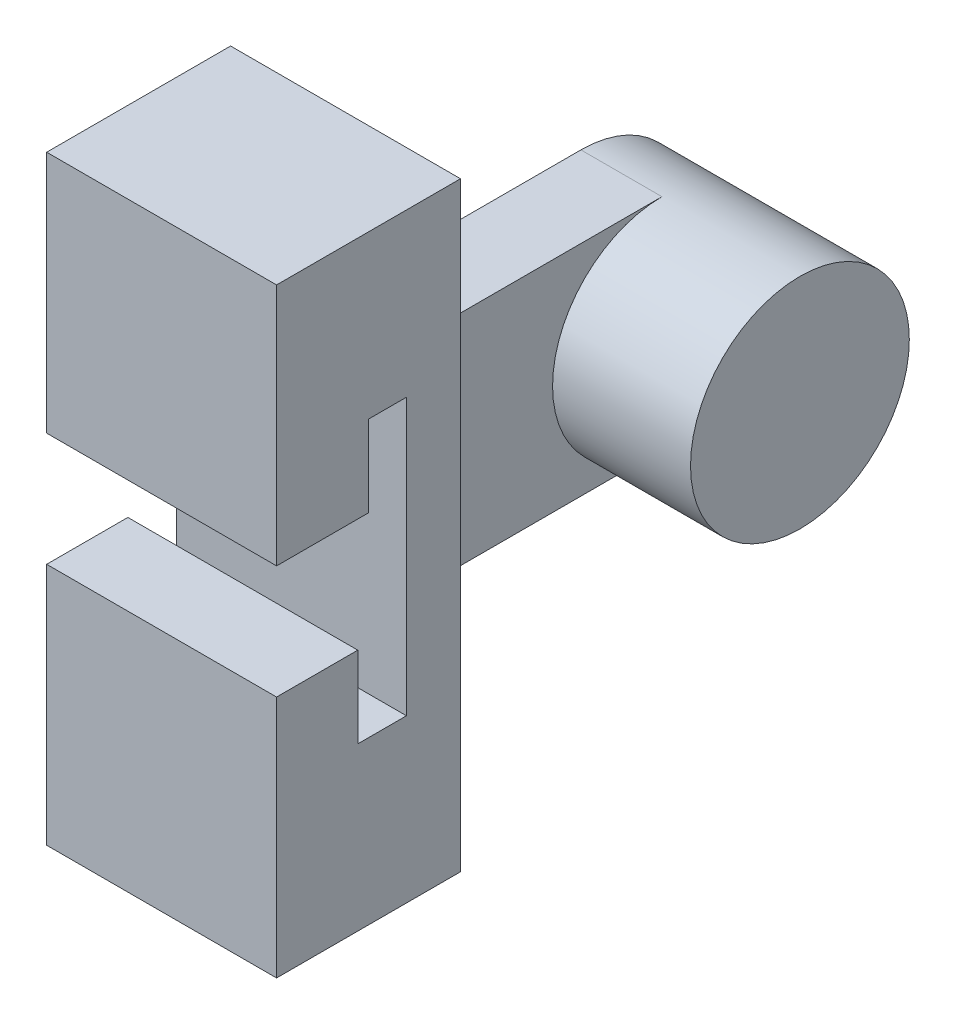
SolidWorks part; units mm, degrees
material "ASTM A36 Steel"
ref_plane "Front Plane" through (0, 0, 0) normal (1, 0, 0) x (0, 1, 0)
ref_plane "Top Plane" through (0, 0, 0) normal (0, 0, 1) x (0, 1, 0)
ref_plane "Right Plane" through (0, 0, 0) normal (0, 1, 0) x (-1, 0, 0)
sketch "Sketch1" plane through (0, 0, 0) normal (1, 0, 0) x (0, 1, 0)
  circle A0 centre (0, 0) radius 30.2184
  dimension "D1" = 30.2184
extrude "Boss-Extrude1" add sketch "Sketch1" along normal blind 38.1
sketch "Sketch2" plane through (0, 0, 0) normal (-1, 0, 0) x (0, -1, 0)
  line L0 (55, 0) -> (-55, 0) construction
  line L1 (-30.2184, 0) -> (-30.2184, 76.2)
  line L2 (-30.2184, 76.2) -> (30.2184, 76.2)
  line L3 (30.2184, 76.2) -> (30.2184, 0)
  arc A0 (-30.2184, 0) -> (30.2184, 0) centre (0, 0) ccw
  circle A1 centre (0, 0) radius 30.2184 construction
  dimension "D2" = 76.2
extrude "Boss-Extrude2" add sketch "Sketch2" along normal blind 22.3947
sketch "Sketch4" plane through (0, 0, 76.2) normal (0, 0, 1) x (1, 0, 0)
  line L0 (-11.1973, 30.2184) -> (-11.1973, -30.2184) construction
  line L1 (-22.3947, 30.2184) -> (0, 30.2184) construction
  line L2 (-22.3947, -30.2184) -> (0, -30.2184) construction
  line L4 (0, -55) -> (0, 55) construction
  line L5 (-42.9473, 38.1) -> (-42.9473, -38.1)
  line L6 (-42.9473, -38.1) -> (20.5527, -38.1)
  line L7 (20.5527, -38.1) -> (20.5527, 38.1)
  line L8 (20.5527, 38.1) -> (-42.9473, 38.1)
  line L9 (55, 0) -> (-55, 0) construction
  dimension "D1" = 11.1973
  dimension "D2" = 31.75
  dimension "D3" = 38.1
  dimension "D4" = 63.5
  dimension "D5" = 76.2
extrude "Boss-Extrude4" add sketch "Sketch4" along normal blind 14.9298
sketch3d "3DSketch1"
  point P0 (-33.4324, 15.0066, 91.1298)
sketch3d "3DSketch2"
  point P0 (-32.8005, -21.279, 91.1298)
sketch "Sketch5" plane through (0, 38.1, 0) normal (0, 1, 0) x (-1, 0, 0)
  line L0 (-20.5527, 76.2) -> (42.9473, 76.2)
  line L1 (42.9473, 76.2) -> (42.9473, 127)
  line L2 (42.9473, 127) -> (-20.5527, 127)
  line L3 (-20.5527, 127) -> (-20.5527, 76.2)
  dimension "D1" = 50.8
extrude "Boss-Extrude5" add sketch "Sketch5" along normal blind 44.7893
mirror "Mirror1" about plane through (0, 0, 0) normal (0, 1, 0) of "Boss-Extrude5"
sketch "Sketch7" plane through (0, 38.1, 0) normal (0, -1, 0) x (1, 0, 0)
  line L0 (-42.9473, 127) -> (20.5527, 127)
  line L1 (20.5527, 127) -> (20.5527, 101.6)
  line L2 (20.5527, 127) -> (20.5527, 91.1298) construction
  line L3 (20.5527, 101.6) -> (-42.9473, 101.6)
  line L4 (-42.9473, 91.1298) -> (-42.9473, 127) construction
  line L5 (-42.9473, 101.6) -> (-42.9473, 127)
  dimension "D1" = 25.4
  dimension "D2" = 63.5
extrude "Boss-Extrude7" add sketch "Sketch7" along normal blind 22.418
sketch "Sketch8" plane through (0, -38.1, 0) normal (0, 1, 0) x (-1, 0, 0)
  line L7 (42.9473, 91.1298) -> (42.9473, 127) construction
  line L8 (-20.5527, 127) -> (42.9473, 127)
  line L9 (-20.5527, 127) -> (-20.5527, 104.5743)
  line L10 (-20.5527, 104.5743) -> (42.9473, 104.5743)
  line L11 (42.9473, 127) -> (42.9473, 104.5743)
  dimension "D1" = 22.4257
extrude "Boss-Extrude8" add sketch "Sketch8" along normal blind 22.418
equation "\"force\"= 800"
equation "\"safetyfactor\"= 4"
equation "\"yieldstrength\"= 3629.43442"
equation "\"E\"= 29007547.43"
equation "\"lengthA\"= 1.5"
equation "\"moduliz\"= ( \"safetyfactor\" * \"lengthA\" * ( \"force\" * 2 ) ) / ( 2 * \"yieldstrength\" )"
equation "\"ra\"= ( 4 * \"moduliz\" / pi ) ^ ( 1 / 3 )"
equation "\"barea\"= ( \"force\" * \"safetyfactor\" ) / ( \"yieldstrength\" )"
equation "\"bthick\"= \"barea\" / \"wb\""
equation "\"wb\"= 1"
equation "\"lc\"= 3"
equation "\"carea\"= ( ( \"force\" * 2 ) * \"safetyfactor\" ) / \"yieldstrength\""
equation "\"hc\"= \"carea\" / \"lc\""
equation "\"hd\"= 0.5"
equation "\"darea\"= ( \"force\" * \"safetyfactor\" ) / \"yieldstrength\""
equation "\"ld\"= \"darea\" / \"hd\""
equation "\"le\"=1"
equation "\"earea\"= ( 2 * \"force\" * \"safetyfactor\" ) / \"yieldstrength\""
equation "\"he\"= \"earea\" / \"le\""
equation "\"D1@Sketch1\"=\"ra\""
equation "\"D1@Boss-Extrude1\"=\"lengthA\""
equation "\"D1@Boss-Extrude2\"=\"bthick\""
equation "\"D4@Sketch4\"=2.5"
equation "\"D5@Sketch4\"=\"lc\""
equation "\"D1@Boss-Extrude4\"=\"hc\""
equation "\"D1@Boss-Extrude5\"=\"ld\""
equation "\"D1@Sketch7\"=\"le\""
